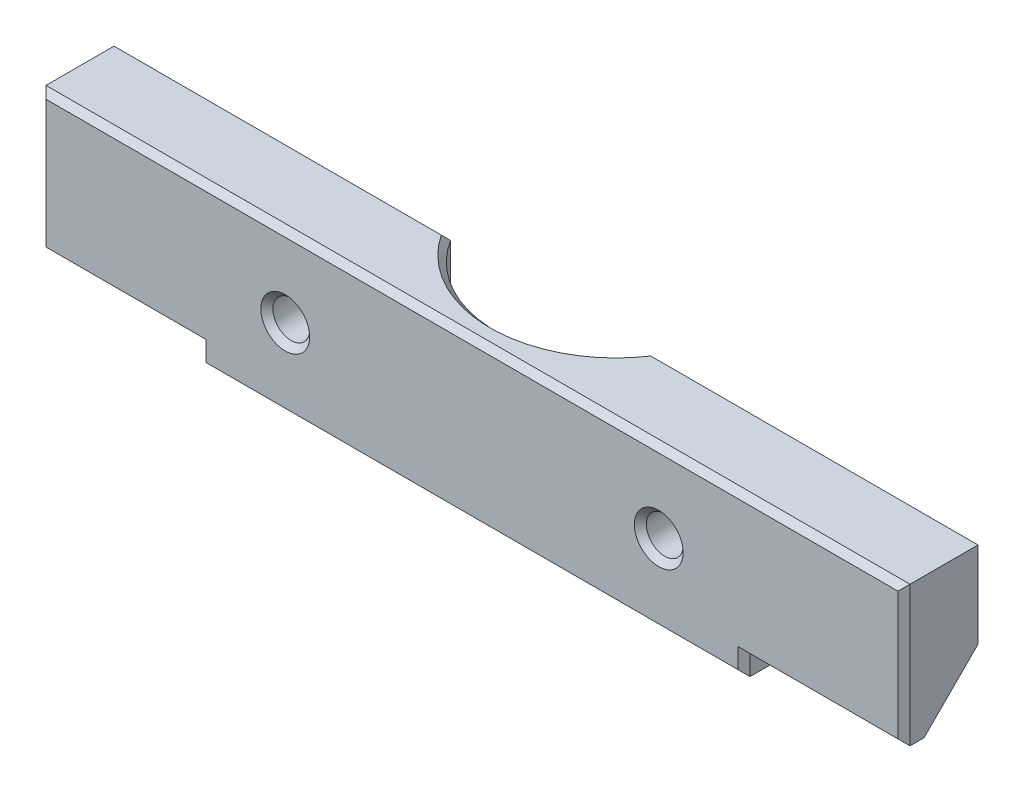
SolidWorks part; units mm, degrees
ref_plane "Front" through (0, 0, 0) normal (0, 0, 1) x (1, 0, 0)
ref_plane "Top" through (0, 0, 0) normal (0, 1, 0) x (1, 0, 0)
ref_plane "Right" through (0, 0, 0) normal (1, 0, 0) x (0, 0, -1)
sketch "Skizze1" plane through (0, 0, 0) normal (0, 0, 1) x (1, 0, 0)
  line L0 (0, 0) -> (0, 36.2286) construction
  line L1 (34, 0) -> (-34, 0)
  line L2 (-34, 0) -> (-34, 20)
  line L3 (-34, 20) -> (34, 20)
  line L4 (34, 0) -> (34, 20)
  point P7 (0, 20)
  dimension "D1" = 20
extrude "Aufsatz-Linear austragen1" add sketch "Skizze1" along normal blind 10
sketch "Skizze2" plane through (-34, 0, 0) normal (-1, 0, 0) x (0, 0, 1)
  line L0 (10, 0) -> (0, 10)
  line L1 (0, 20) -> (0, 0) construction
  line L2 (0, 10) -> (0, 20)
  line L3 (0, 20) -> (10, 20)
  line L4 (10, 20) -> (10, 0)
extrude "Aufsatz-Linear austragen2" add sketch "Skizze2" along normal blind 20
mirror "Spiegeln1" about plane through (0, 0, 0) normal (1, 0, 0) of "Aufsatz-Linear austragen2"
sketch "Skizze3" plane through (0, 0, 0) normal (0, -1, 0) x (1, 0, 0)
  line L0 (0, 0) -> (0, -17.264) construction
  circle A0 centre (0, -8) radius 15
  dimension "D1" = 30
extrude "Schnitt-Linear austragen1" cut sketch "Skizze3" against normal blind 20
sketch "Skizze4" plane through (0, 0, 0) normal (0, 0, -1) x (-1, 0, 0)
  line L0 (-12.6886, 10) -> (-34, 10) construction
  line L4 (-12.6886, 0) -> (-12.6886, 20) construction
  line L5 (0, 0) -> (0, 20) construction
  line L6 (-12.6886, 0) -> (12.6886, 0) construction
  line L7 (12.6886, 20) -> (-12.6886, 20) construction
  circle A1 centre (-23.3443, 10) radius 2.3
  circle A2 centre (23.3443, 10) radius 2.3
  dimension "D1" = 4.6
extrude "Schnitt-Linear austragen2" cut sketch "Skizze4" against normal blind 20
sketch "Skizze5" plane through (0, 0, 0) normal (0, 0, -1) x (-1, 0, 0)
  circle A0 centre (-23.3443, 10) radius 3.75
  circle A1 centre (23.3443, 10) radius 3.75
  dimension "D1" = 7.5
extrude "Schnitt-Linear austragen3" cut sketch "Skizze5" against normal blind 3
sketch "Skizze6" plane through (-54, 0, 0) normal (-1, 0, 0) x (0, 0, 1)
  line L0 (10, 2.5) -> (4.8526, 2.5)
  line L1 (10, 0) -> (10, 20) construction
  line L2 (4.8526, 2.5) -> (4.8526, -2.6686)
  line L3 (4.8526, -2.6686) -> (13.5868, -2.7881)
  line L4 (13.5868, -2.7881) -> (13.5868, 2.151)
  line L5 (13.5868, 2.151) -> (10, 2.5)
  dimension "D1" = 2.5
extrude "Schnitt-Linear austragen4" cut sketch "Skizze6" against normal blind 20
mirror "Spiegeln3" about plane through (0, 0, 0) normal (1, 0, 0) of "Schnitt-Linear austragen4"
chamfer "Fase3" distance 0.75 angle 45 22 edges at (0, 0, 10) (-34, 1.25, 10) (-44, 2.5, 10) (-54, 11.25, 10) (0, 20, 10) (54, 11.25, 10) (44, 2.5, 10) (34, 1.25, 10) (-21.0443, 10, 10) (25.6443, 10, 10) (-27.0943, 10, 0) (19.5943, 10, 0) (54, 15, 0) (33.3443, 20, 0) (0, 20, 7) (-33.3443, 20, 0) (-54, 15, 0) (34, 5, 0) (23.3443, 0, 0) (0, 0, 7) (-34, 5, 0) (-23.3443, 0, 0)
